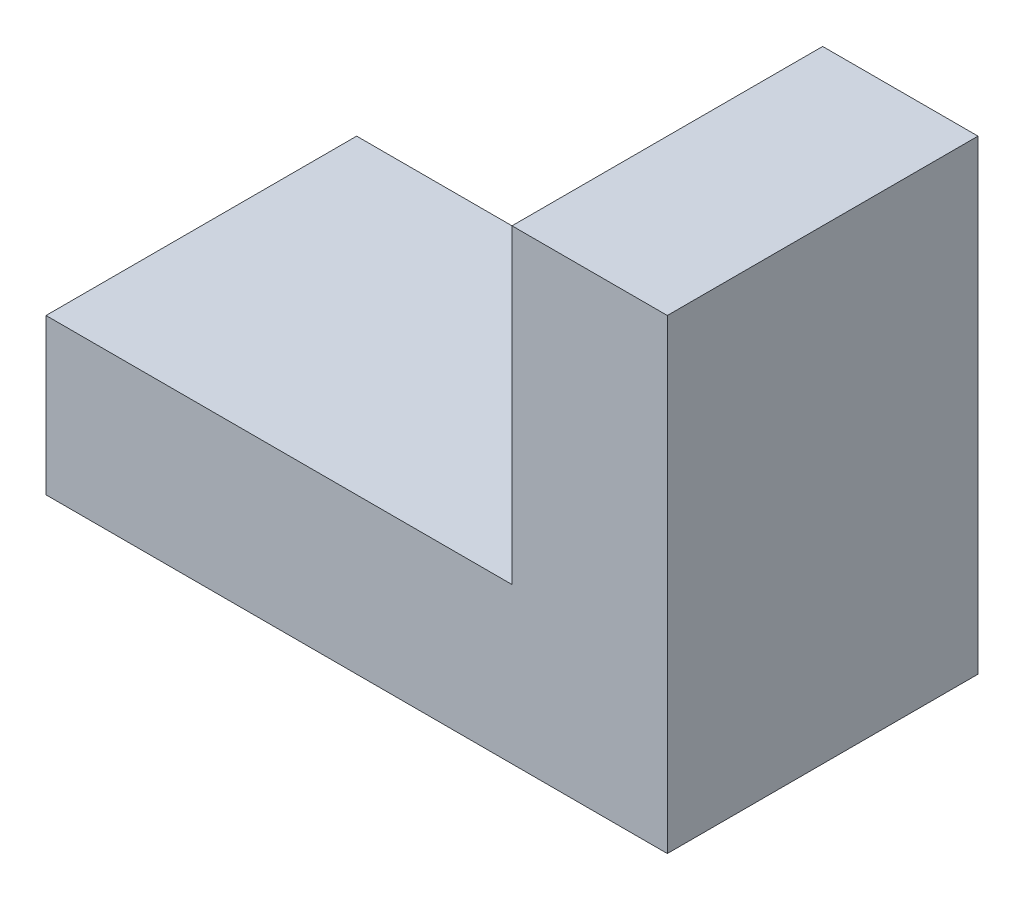
SolidWorks part; units mm, degrees
ref_plane "Front Plane" through (0, 0, 0) normal (0, 0, 1) x (1, 0, 0)
ref_plane "Top Plane" through (0, 0, 0) normal (0, 1, 0) x (1, 0, 0)
ref_plane "Right Plane" through (0, 0, 0) normal (1, 0, 0) x (0, 0, -1)
ref_plane "Plane1" through (0, 0, 20) normal (0, 0, -1) x (-1, 0, 0)
sketch "Sketch1" plane through (0, 0, 20) normal (0, 0, -1) x (-1, 0, 0)
  line L0 (5, 5) -> (25, 5)
  line L1 (25, 5) -> (25, 10)
  line L2 (25, 10) -> (10, 10)
  line L3 (10, 10) -> (10, 20)
  line L4 (10, 20) -> (5, 20)
  line L5 (5, 20) -> (5, 5)
extrude "Boss-Extrude1" add sketch "Sketch1" along normal blind 10
